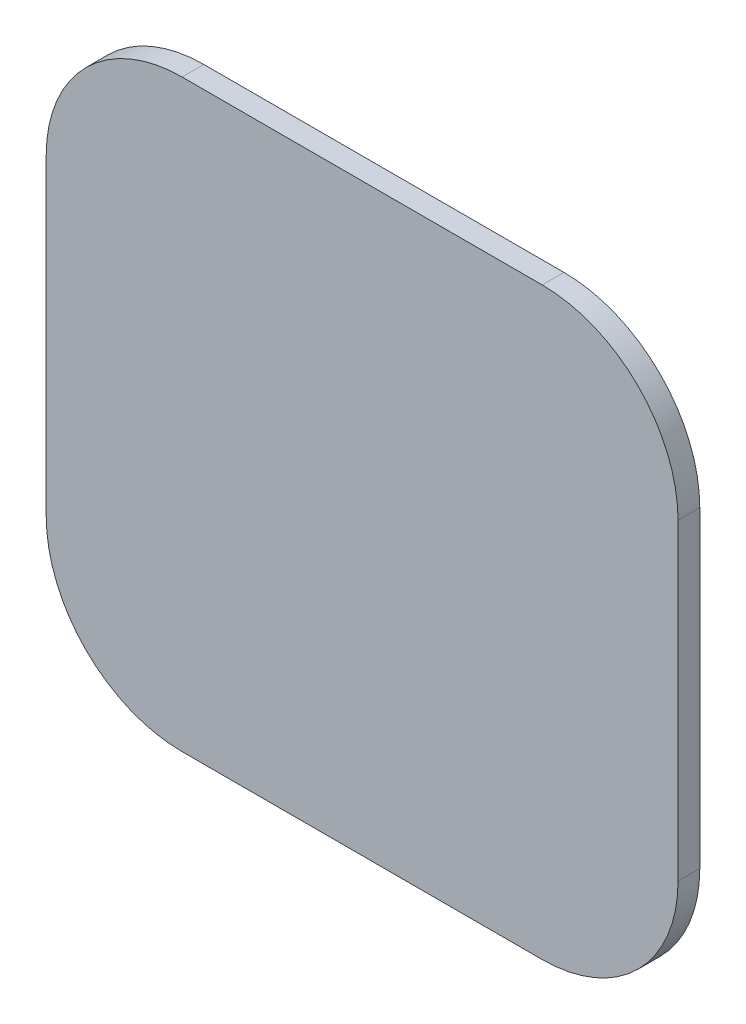
SolidWorks part; units mm, degrees
ref_plane "Plano frontal" through (0, 0, 0) normal (0, 0, 1) x (1, 0, 0)
ref_plane "Plano superior" through (0, 0, 0) normal (0, 1, 0) x (1, 0, 0)
ref_plane "Plano direito" through (0, 0, 0) normal (1, 0, 0) x (0, 0, -1)
sketch "Esboço1" plane through (0, 0, 0) normal (0, 0, 1) x (1, 0, 0)
  line L1 (-10, 0) -> (-36.5, 0)
  line L2 (0, 10) -> (0, 33)
  line L3 (-10, 43) -> (-36.5, 43)
  line L4 (-46.5, 10) -> (-46.5, 33)
  arc A0 (-36.5, 43) -> (-46.5, 33) centre (-36.5, 33) ccw
  arc A1 (-36.5, 0) -> (-46.5, 10) centre (-36.5, 10) cw
  arc A2 (-10, 0) -> (0, 10) centre (-10, 10) ccw
  arc A3 (0, 33) -> (-10, 43) centre (-10, 33) ccw
  point P7 (-46.5, 43)
  point P10 (-46.5, 0)
  point P13 (0, 0)
  point P16 (0, 43)
  dimension "D3" = 10
  dimension "D1" = 43
  dimension "D2" = 46.5
extrude "Ressalto-extrusão1" add sketch "Esboço1" along normal blind 1.6
ref_plane "Plano2" through (0, 0, 21.6) normal (0, 0, 1) x (1, 0, 0)
